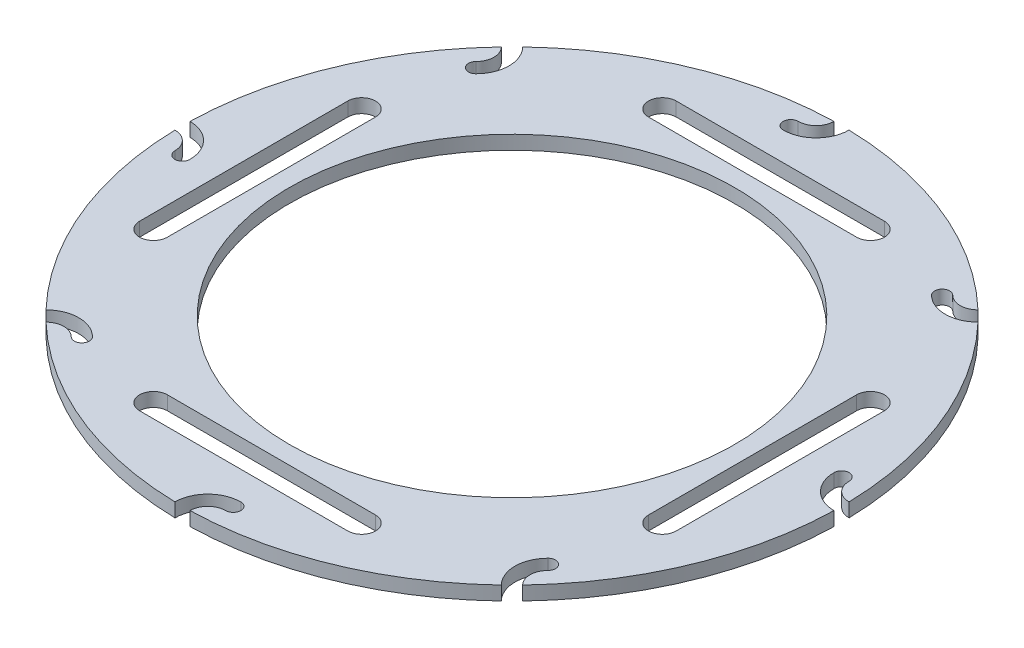
SolidWorks part; units mm, degrees
ref_plane "Front Plane" through (0, 0, 0) normal (0, 0, 1) x (1, 0, 0)
ref_plane "Top Plane" through (0, 0, 0) normal (0, 1, 0) x (1, 0, 0)
ref_plane "Right Plane" through (0, 0, 0) normal (1, 0, 0) x (0, 0, -1)
sketch "Sketch1" plane through (0, 0, 0) normal (0, 1, 0) x (1, 0, 0)
  line L0 (11, -4.5) -> (11, 4.5) construction
  line L1 (10.4, -4.5) -> (10.4, 4.5)
  line L2 (11.6, -4.5) -> (11.6, 4.5)
  line L3 (0, 0) -> (0, -14.25) construction
  line L4 (-4.5, -11) -> (4.5, -11) construction
  line L7 (9.8465, -8.2908) -> (10.3061, -8.7504) construction
  line L8 (10.0763, -10.0763) -> (10.8541, -9.2985) construction
  line L9 (1.1, -12.825) -> (1.1, -13.475) construction
  line L10 (0, -14.25) -> (1.1, -14.25) construction
  line L11 (-8.2908, -9.8465) -> (-8.7504, -10.3061) construction
  line L12 (-10.0763, -10.0763) -> (-9.2985, -10.8541) construction
  line L13 (-12.825, -1.1) -> (-13.475, -1.1) construction
  line L14 (-14.25, 0) -> (-14.25, -1.1) construction
  line L15 (-9.8465, 8.2908) -> (-10.3061, 8.7504) construction
  line L16 (-10.0763, 10.0763) -> (-10.8541, 9.2985) construction
  line L17 (-1.1, 12.825) -> (-1.1, 13.475) construction
  line L18 (0, 14.25) -> (-1.1, 14.25) construction
  line L19 (12.825, 1.1) -> (13.475, 1.1) construction
  line L20 (8.2908, 9.8465) -> (8.7504, 10.3061) construction
  line L21 (10.0763, 10.0763) -> (9.2985, 10.8541) construction
  line L23 (-4.5, -10.4) -> (4.5, -10.4)
  line L24 (-4.5, -11.6) -> (4.5, -11.6)
  line L25 (-11, 4.5) -> (-11, -4.5) construction
  line L26 (-10.4, 4.5) -> (-10.4, -4.5)
  line L27 (-11.6, 4.5) -> (-11.6, -4.5)
  line L28 (4.5, 11) -> (-4.5, 11) construction
  line L29 (4.5, 10.4) -> (-4.5, 10.4)
  line L30 (4.5, 11.6) -> (-4.5, 11.6)
  line L31 (14.25, 0) -> (14.25, 1.1) construction
  circle A0 centre (0, 0) radius 14.25
  circle A1 centre (0, 0) radius 9.625
  arc A2 (10.4, -4.5) -> (11.6, -4.5) centre (11, -4.5) ccw
  arc A3 (11.6, 4.5) -> (10.4, 4.5) centre (11, 4.5) ccw
  arc A7 (9.8465, -8.2908) -> (10.3061, -8.7504) centre (10.0763, -8.5206) cw
  arc A8 (9.8438, -10.3035) -> (9.8465, -8.2908) centre (10.8541, -9.2985) cw
  arc A9 (10.3035, -9.8438) -> (10.3061, -8.7504) centre (10.8541, -9.2985) cw
  arc A10 (1.1, -12.825) -> (1.1, -13.475) centre (1.1, -13.15) cw
  arc A11 (-0.325, -14.2463) -> (1.1, -12.825) centre (1.1, -14.25) cw
  arc A12 (12.825, 1.1) -> (13.475, 1.1) centre (13.15, 1.1) cw
  arc A13 (0.325, -14.2463) -> (1.1, -13.475) centre (1.1, -14.25) cw
  arc A14 (-4.5, -10.4) -> (-4.5, -11.6) centre (-4.5, -11) ccw
  arc A15 (4.5, -11.6) -> (4.5, -10.4) centre (4.5, -11) ccw
  arc A16 (-10.4, 4.5) -> (-11.6, 4.5) centre (-11, 4.5) ccw
  arc A17 (-11.6, -4.5) -> (-10.4, -4.5) centre (-11, -4.5) ccw
  arc A18 (4.5, 10.4) -> (4.5, 11.6) centre (4.5, 11) ccw
  arc A19 (-4.5, 11.6) -> (-4.5, 10.4) centre (-4.5, 11) ccw
  arc A20 (14.2463, -0.325) -> (12.825, 1.1) centre (14.25, 1.1) cw
  arc A21 (14.2463, 0.325) -> (13.475, 1.1) centre (14.25, 1.1) cw
  arc A22 (-8.2908, -9.8465) -> (-8.7504, -10.3061) centre (-8.5206, -10.0763) cw
  arc A23 (-10.3035, -9.8438) -> (-8.2908, -9.8465) centre (-9.2985, -10.8541) cw
  arc A24 (-9.8438, -10.3035) -> (-8.7504, -10.3061) centre (-9.2985, -10.8541) cw
  arc A25 (-12.825, -1.1) -> (-13.475, -1.1) centre (-13.15, -1.1) cw
  arc A26 (-14.2463, 0.325) -> (-12.825, -1.1) centre (-14.25, -1.1) cw
  arc A27 (-14.2463, -0.325) -> (-13.475, -1.1) centre (-14.25, -1.1) cw
  arc A28 (-9.8465, 8.2908) -> (-10.3061, 8.7504) centre (-10.0763, 8.5206) cw
  arc A29 (-9.8438, 10.3035) -> (-9.8465, 8.2908) centre (-10.8541, 9.2985) cw
  arc A30 (-10.3035, 9.8438) -> (-10.3061, 8.7504) centre (-10.8541, 9.2985) cw
  arc A31 (-1.1, 12.825) -> (-1.1, 13.475) centre (-1.1, 13.15) cw
  arc A32 (0.325, 14.2463) -> (-1.1, 12.825) centre (-1.1, 14.25) cw
  arc A33 (-0.325, 14.2463) -> (-1.1, 13.475) centre (-1.1, 14.25) cw
  arc A34 (8.2908, 9.8465) -> (8.7504, 10.3061) centre (8.5206, 10.0763) cw
  arc A35 (10.3035, 9.8438) -> (8.2908, 9.8465) centre (9.2985, 10.8541) cw
  arc A36 (9.8438, 10.3035) -> (8.7504, 10.3061) centre (9.2985, 10.8541) cw
  point P6 (11, 0)
  point P17 (0, -11)
  point P61 (0, 0)
  point P65 (-11, 0)
  point P72 (0, 11)
  point P77 (0, 0)
  point P102 (0, 0)
  dimension "D1" = 28.5
  dimension "D2" = 19.25
  dimension "D6" = 8
  dimension "D7" = 4
  dimension "D3" = 1.2
  dimension "D4" = 9
  dimension "D5" = 11
  dimension "D8" = 0.65
  dimension "D9" = 0.325
  dimension "D10" = 1.1
extrude "Boss-Extrude1" add sketch "Sketch1" along normal blind 0.6
ref_plane "Plane1" through (0, 0.3, 0) normal (0, 1, 0) x (1, 0, 0)
sketch "Sketch2" plane through (0, 0.3, 0) normal (0, 1, 0) x (1, 0, 0)
  point P4 (13.75, 0)
  point P5 (9.7227, -9.7227)
  point P8 (0, -13.75)
  point P9 (-9.7227, -9.7227)
  point P10 (-13.75, 0)
  point P11 (-9.7227, 9.7227)
  point P12 (0, 13.75)
  point P13 (9.7227, 9.7227)
  point P14 (0, 0)
  dimension "D1" = 8
ref_plane "Plane4" through (0.408, 0, 0.3764) normal (-0.7351, 0, -0.678) x (-0.678, 0, 0.7351)
ref_plane "Plane5" through (-0.3764, 0, 0.408) normal (0.678, 0, -0.7351) x (-0.7351, 0, -0.678)
ref_point "Point1"
ref_point "Point2"
